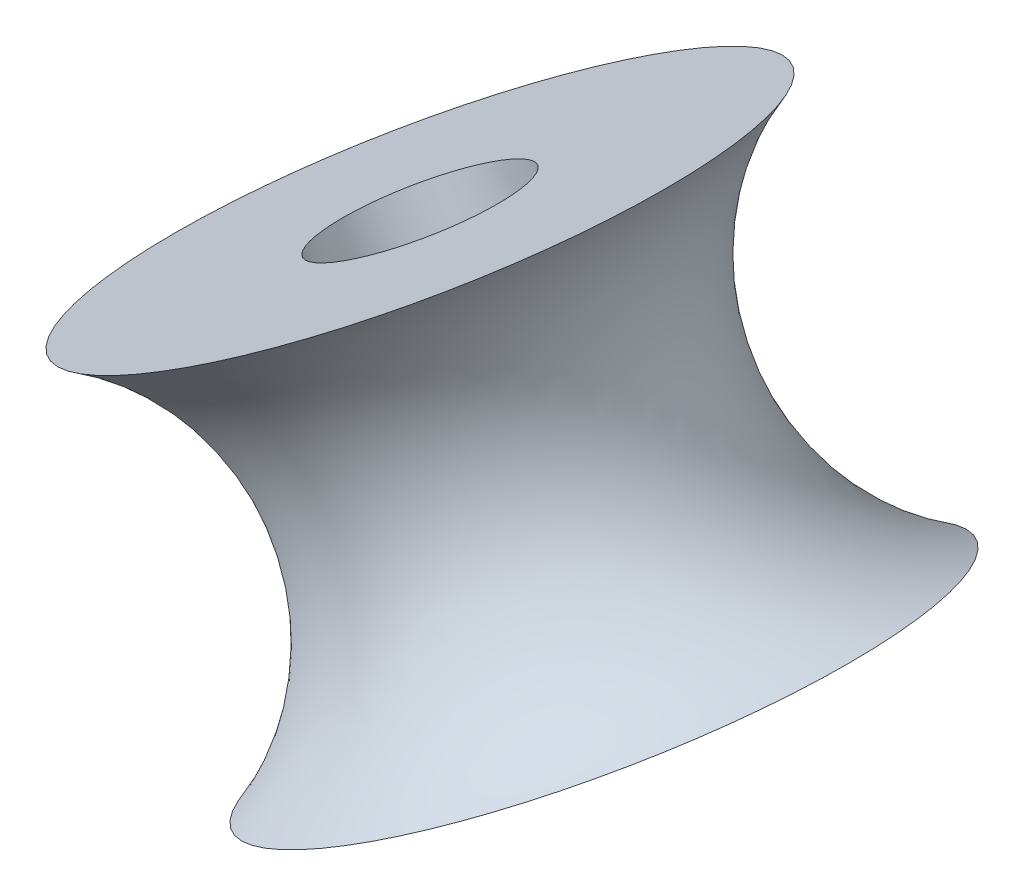
SolidWorks part; units mm, degrees
ref_plane "Front Plane" through (0, 0, 0) normal (0, 0, 1) x (1, 0, 0)
ref_plane "Top Plane" through (0, 0, 0) normal (0, 1, 0) x (1, 0, 0)
ref_plane "Right Plane" through (0, 0, 0) normal (1, 0, 0) x (0, 0, -1)
sketch "Sketch1" plane through (0, 0, 0) normal (0, 0, 1) x (1, 0, 0)
  line L7 (-0.4233, 5.9332) -> (4.9267, -3.3332)
  line L8 (4.4471, 8.7452) -> (-0.4233, 5.9332)
  line L9 (9.7971, -0.5213) -> (4.9267, -3.3332)
  line L10 (-2.675, 4.6332) -> (2.675, -4.6332) construction
  arc A3 (4.4471, 8.7452) -> (9.7971, -0.5213) centre (10.0844, 5.8222) ccw
revolve "Revolve2" add sketch "Sketch1" angle 360 about L10
